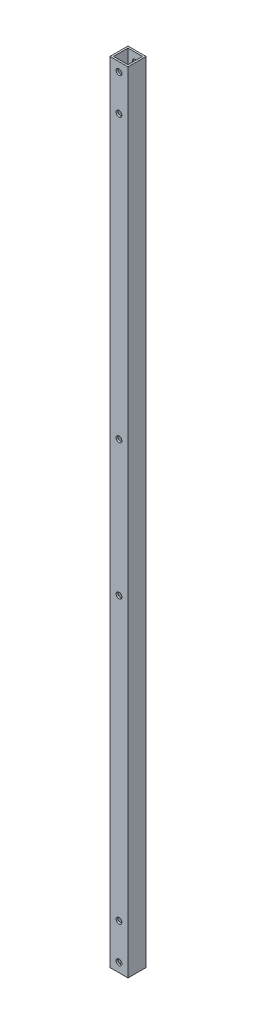
SolidWorks part; units mm, degrees
ref_plane "正面" through (0, 0, 0) normal (0, 0, 1) x (1, 0, 0)
ref_plane "平面" through (0, 0, 0) normal (0, 1, 0) x (1, 0, 0)
ref_plane "右側面" through (0, 0, 0) normal (1, 0, 0) x (0, 0, -1)
sketch "ｽｹｯﾁ1" plane through (0, 0, 0) normal (0, 1, 0) x (1, 0, 0)
  line L0 (-4, 4) -> (4, 4)
  line L1 (-5, 5) -> (5, 5)
  line L2 (-5, 5) -> (-5, -5)
  line L3 (-5, -5) -> (5, -5)
  line L4 (5, 5) -> (5, -5)
  line L5 (-5, 5) -> (5, -5) construction
  line L6 (-5, -5) -> (5, 5) construction
  line L7 (4, 4) -> (4, -4)
  line L8 (-4, -4) -> (4, -4)
  line L9 (-4, 4) -> (-4, -4)
  point P0 (0, 0)
  dimension "D1" = 10
  dimension "D2" = 1
extrude "ﾎﾞｽ - 押し出し1" add sketch "ｽｹｯﾁ1" along normal mid plane 437.43
sketch "ｽｹｯﾁ2" plane through (0, 0, 5) normal (0, 0, 1) x (1, 0, 0)
  line L0 (0, 218.715) -> (0, 213.715) construction
  line L1 (-5, 218.715) -> (5, 218.715) construction
  line L2 (0, 213.715) -> (0, 193.715) construction
  circle A0 centre (0, 213.715) radius 1.6
  circle A1 centre (0, 193.715) radius 1.6
  dimension "D3" = 3.2
  dimension "D4" = 3.2
  dimension "D1" = 5
  dimension "D2" = 20
extrude "ｶｯﾄ - 押し出し1" cut sketch "ｽｹｯﾁ2" against normal mid plane 427.43
mirror "ﾐﾗｰ1" about plane through (0, 0, 0) normal (0, 1, 0) of "ｶｯﾄ - 押し出し1"
sketch "ｽｹｯﾁ3" plane through (0, 0, 5) normal (0, 0, 1) x (1, 0, 0)
  circle A0 centre (0.005, -37.5792) radius 1.6 construction
  circle A1 centre (0, 37.4208) radius 1.6 construction
  circle A2 centre (0.005, -37.5792) radius 1.6
  circle A3 centre (0, 37.4208) radius 1.6
extrude "ｶｯﾄ - 押し出し2" cut sketch "ｽｹｯﾁ3" against normal blind 10
